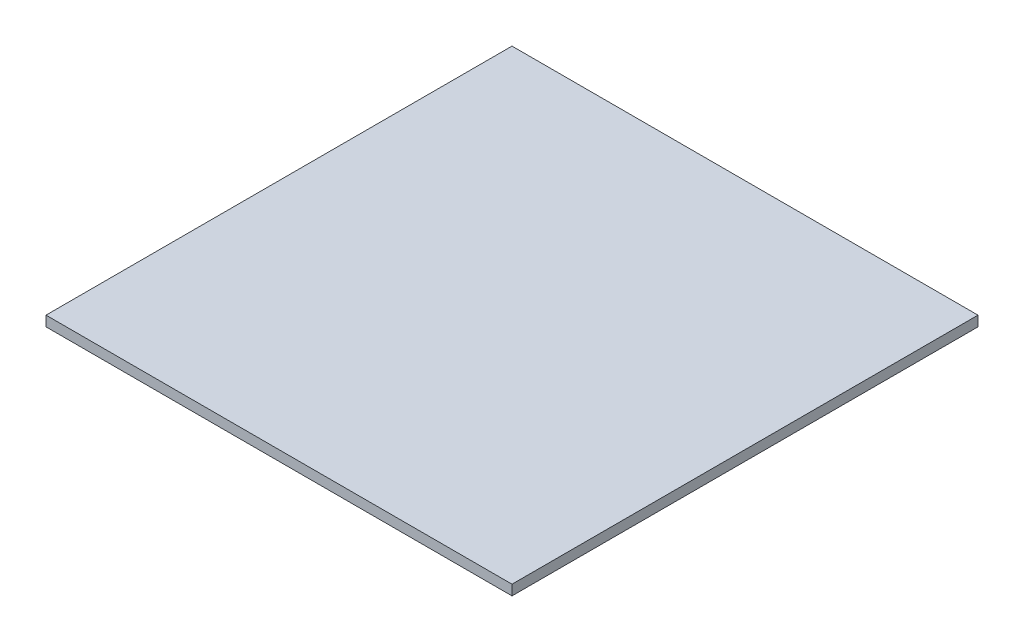
SolidWorks part; units mm, degrees
ref_plane "Front Plane" through (0, 0, 0) normal (0, 0, 1) x (1, 0, 0)
ref_plane "Top Plane" through (0, 0, 0) normal (0, 1, 0) x (1, 0, 0)
ref_plane "Right Plane" through (0, 0, 0) normal (1, 0, 0) x (0, 0, -1)
sketch "Sketch1" plane through (0, 0, 0) normal (0, 1, 0) x (1, 0, 0)
  line L1 (-31.519, 260.0514) -> (260.1786, 260.0514)
  line L2 (-31.519, 260.0514) -> (-31.519, -31.6364)
  line L3 (-31.519, -31.6364) -> (260.1786, -31.6364)
  line L4 (260.1786, 260.0514) -> (260.1786, -31.6364)
extrude "Boss-Extrude1" add sketch "Sketch1" along normal blind 6.3596 contours L2 L1 L4 L3
